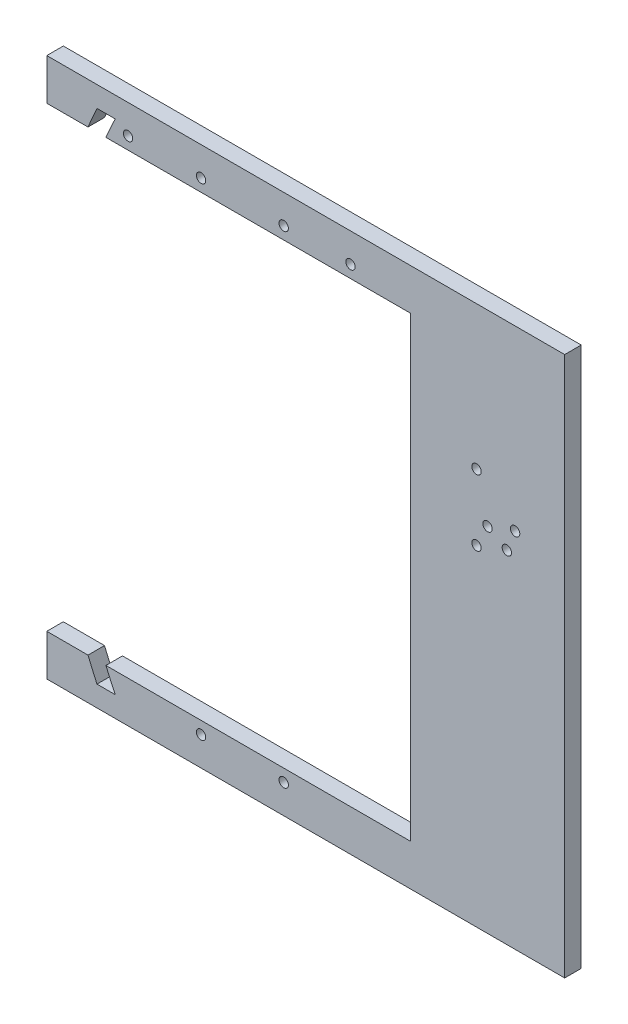
SolidWorks part; units mm, degrees
ref_plane "Front Plane" through (0, 0, 0) normal (0, 0, 1) x (1, 0, 0)
ref_plane "Top Plane" through (0, 0, 0) normal (0, 1, 0) x (1, 0, 0)
ref_plane "Right Plane" through (0, 0, 0) normal (1, 0, 0) x (0, 0, -1)
sketch "Bench Frame Sketch" plane through (0, 0, 0) normal (0, 0, 1) x (1, 0, 0)
  line L0 (-70, -98) -> (118, -98)
  line L1 (118, -98) -> (118, 98)
  line L2 (118, 98) -> (-70, 98)
  line L3 (-70, 98) -> (-70, 83)
  line L4 (-70, 83) -> (62, 83)
  line L5 (62, 83) -> (62, -83)
  line L6 (62, -83) -> (-70, -83)
  line L7 (-70, -83) -> (-70, -98)
  dimension "D1" = 70
  dimension "D2" = 118
  dimension "D3" = 62
  dimension "D4" = 98
  dimension "D5" = 98
  dimension "D6" = 83
  dimension "D7" = 83
extrude "Bench Frame Extrude" add sketch "Bench Frame Sketch" along normal mid plane 6
sketch "Curved Panel Clearance Sketch" plane through (0, 0, 0) normal (0, 0, 1) x (1, 0, 0)
  line L0 (-51.7777, 90.5) -> (-45.1596, 90.5)
  line L1 (-45.1596, -90.5) -> (-51.7777, -90.5)
  arc A0 (-51.7777, -90.5) -> (-51.7777, 90.5) centre (146, 0) cw
  arc A1 (-45.1596, 90.5) -> (-45.1596, -90.5) centre (146, 0) ccw
  dimension "D2" = 217.5
  dimension "D3" = 211.5
  dimension "D1" = 146
  dimension "D4" = 90.5
  dimension "D5" = 90.5
extrude "Curved Panel Clearance" cut sketch "Curved Panel Clearance Sketch" against normal mid plane 8
sketch "Pod Foot Clearance Sketch" plane through (0, 0, 0) normal (0, 0, 1) x (1, 0, 0)
  circle A0 centre (-14, -87.5) radius 1.7
  circle A1 centre (16, -87.5) radius 1.7
  circle A2 centre (-14, 87.5) radius 1.7
  circle A3 centre (16, 87.5) radius 1.7
  circle A4 centre (40.25, 87.5) radius 1.7
  circle A5 centre (-40.5, 87.5) radius 1.7
  circle A6 centre (86, 22) radius 1.7
  circle A7 centre (86, 46) radius 1.7
  circle A8 centre (90, 30) radius 1.7
  circle A9 centre (97, 26) radius 1.7
  circle A10 centre (100, 33.5) radius 1.7
  dimension "D3" = 3.4
  dimension "D6" = 3.4
  dimension "D9" = 3.4
  dimension "D12" = 3.4
  dimension "D15" = 3.4
  dimension "D18" = 3.4
  dimension "D21" = 3.4
  dimension "D24" = 3.4
  dimension "D27" = 3.4
  dimension "D30" = 3.4
  dimension "D33" = 3.4
  dimension "D1" = 14
  dimension "D2" = 87.5
  dimension "D4" = 16
  dimension "D5" = 87.5
  dimension "D7" = 14
  dimension "D8" = 87.5
  dimension "D10" = 16
  dimension "D11" = 87.5
  dimension "D13" = 40.25
  dimension "D14" = 87.5
  dimension "D16" = 40.5
  dimension "D17" = 87.5
  dimension "D19" = 86
  dimension "D20" = 22
  dimension "D22" = 86
  dimension "D23" = 46
  dimension "D25" = 90
  dimension "D26" = 30
  dimension "D28" = 97
  dimension "D29" = 26
  dimension "D31" = 100
  dimension "D32" = 33.5
extrude "Pod Foot Through Holes" cut sketch "Pod Foot Clearance Sketch" against normal mid plane 8
ref_plane "Bench Underside Plane" through (0, 0, -3) normal (0, 0, 1) x (1, 0, 0)
sketch "Foot Counterbore Sketch" plane through (0, 0, -3) normal (0, 0, 1) x (1, 0, 0)
  circle A0 centre (-14, -87.5) radius 3.6
  circle A1 centre (16, -87.5) radius 3.6
  circle A2 centre (-14, 87.5) radius 3.6
  circle A3 centre (16, 87.5) radius 3.6
  circle A4 centre (40.25, 87.5) radius 3.6
  circle A5 centre (-40.5, 87.5) radius 3.6
  circle A6 centre (86, 22) radius 3.6
  circle A7 centre (86, 46) radius 3.6
  circle A8 centre (90, 30) radius 3.6
  circle A9 centre (97, 26) radius 3.6
  circle A10 centre (100, 33.5) radius 3.6
  dimension "D1" = 14
  dimension "D2" = 87.5
  dimension "D4" = 16
  dimension "D5" = 87.5
  dimension "D7" = 14
  dimension "D8" = 87.5
  dimension "D10" = 16
  dimension "D11" = 87.5
  dimension "D13" = 40.25
  dimension "D14" = 87.5
  dimension "D16" = 40.5
  dimension "D17" = 87.5
  dimension "D19" = 86
  dimension "D20" = 22
  dimension "D22" = 86
  dimension "D23" = 46
  dimension "D25" = 90
  dimension "D26" = 30
  dimension "D28" = 97
  dimension "D29" = 26
  dimension "D31" = 100
  dimension "D32" = 33.5
  dimension "D3" = 7.2
  dimension "D6" = 7.2
  dimension "D9" = 7.2
  dimension "D12" = 7.2
  dimension "D15" = 7.2
  dimension "D18" = 7.2
  dimension "D21" = 7.2
  dimension "D24" = 7.2
  dimension "D27" = 7.2
  dimension "D30" = 7.2
  dimension "D33" = 7.2
extrude "Foot Counterbores" cut sketch "Foot Counterbore Sketch" along normal blind 2.9
equation "\"guard_front_foot_x\"= 14mm 'Front wall foot offset toward -X"
equation "\"guard_rear_foot_x\"= 16mm 'Rear wall foot offset toward +X"
equation "\"guard_foot_y\"= 87.5mm 'Wall and ear foot transverse location"
equation "\"inner_ear_foot_x\"= 40.25mm 'Inner ear foot at shaft pin"
equation "\"outer_ear_foot_x\"= 40.5mm 'Outer ear foot offset toward -X"
equation "\"tower_foot_1_x\"= 86mm 'Tower foot screw 1 X"
equation "\"tower_foot_1_y\"= 22mm 'Tower foot screw 1 Y"
equation "\"tower_foot_2_x\"= 86mm 'Tower foot screw 2 X"
equation "\"tower_foot_2_y\"= 46mm 'Tower foot screw 2 Y"
equation "\"tower_foot_3_x\"= 90mm 'Tower foot screw 3 X"
equation "\"tower_foot_3_y\"= 30mm 'Tower foot screw 3 Y"
equation "\"tower_foot_4_x\"= 97mm 'Tower foot screw 4 X"
equation "\"tower_foot_4_y\"= 26mm 'Tower foot screw 4 Y"
equation "\"tower_foot_5_x\"= 100mm 'Tower foot screw 5 X"
equation "\"tower_foot_5_y\"= 33.5mm 'Tower foot screw 5 Y"
equation "\"frame_left\"= 70mm 'Frame open end toward -X"
equation "\"frame_right\"= 118mm 'Frame closed end toward +X"
equation "\"frame_half_width\"= 98mm 'Bench frame half width"
equation "\"opening_end\"= 62mm 'Wheel opening closed end"
equation "\"opening_half_width\"= 83mm 'Wheel opening half width"
equation "\"bench_thickness\"= 6mm 'Bench frame plate thickness"
equation "\"panel_centre_x\"= 146mm 'Robot deck circle centre relative to wheel"
equation "\"relief_outer_radius\"= 217.5mm 'Outer guard panel clearance radius"
equation "\"relief_inner_radius\"= 211.5mm 'Inner guard panel clearance radius"
equation "\"relief_half_width\"= 90.5mm 'Transverse panel clearance extent"
equation "\"clearance_cut_depth\"= 8mm 'Relief cutter extends past both plate faces"
equation "\"screw_clearance\"= 3.4mm 'M3 foot screw clearance"
equation "\"counterbore_diameter\"= 7.2mm 'M3 pan head counterbore"
equation "\"counterbore_depth\"= 2.9mm 'Counterbore from underside"
equation "\"D1@Bench Frame Sketch\"= \"frame_left\""
equation "\"D2@Bench Frame Sketch\"= \"frame_right\""
equation "\"D3@Bench Frame Sketch\"= \"opening_end\""
equation "\"D4@Bench Frame Sketch\"= \"frame_half_width\""
equation "\"D5@Bench Frame Sketch\"= \"frame_half_width\""
equation "\"D6@Bench Frame Sketch\"= \"opening_half_width\""
equation "\"D7@Bench Frame Sketch\"= \"opening_half_width\""
equation "\"D1@Bench Frame Extrude\"= \"bench_thickness\""
equation "\"D1@Curved Panel Clearance Sketch\"= \"panel_centre_x\""
equation "\"D2@Curved Panel Clearance Sketch\"= \"relief_outer_radius\""
equation "\"D3@Curved Panel Clearance Sketch\"= \"relief_inner_radius\""
equation "\"D4@Curved Panel Clearance Sketch\"= \"relief_half_width\""
equation "\"D5@Curved Panel Clearance Sketch\"= \"relief_half_width\""
equation "\"D1@Curved Panel Clearance\"= \"clearance_cut_depth\""
equation "\"D1@Pod Foot Clearance Sketch\"= \"guard_front_foot_x\""
equation "\"D2@Pod Foot Clearance Sketch\"= \"guard_foot_y\""
equation "\"D3@Pod Foot Clearance Sketch\"= \"screw_clearance\""
equation "\"D4@Pod Foot Clearance Sketch\"= \"guard_rear_foot_x\""
equation "\"D5@Pod Foot Clearance Sketch\"= \"guard_foot_y\""
equation "\"D6@Pod Foot Clearance Sketch\"= \"screw_clearance\""
equation "\"D7@Pod Foot Clearance Sketch\"= \"guard_front_foot_x\""
equation "\"D8@Pod Foot Clearance Sketch\"= \"guard_foot_y\""
equation "\"D9@Pod Foot Clearance Sketch\"= \"screw_clearance\""
equation "\"D10@Pod Foot Clearance Sketch\"= \"guard_rear_foot_x\""
equation "\"D11@Pod Foot Clearance Sketch\"= \"guard_foot_y\""
equation "\"D12@Pod Foot Clearance Sketch\"= \"screw_clearance\""
equation "\"D13@Pod Foot Clearance Sketch\"= \"inner_ear_foot_x\""
equation "\"D14@Pod Foot Clearance Sketch\"= \"guard_foot_y\""
equation "\"D15@Pod Foot Clearance Sketch\"= \"screw_clearance\""
equation "\"D16@Pod Foot Clearance Sketch\"= \"outer_ear_foot_x\""
equation "\"D17@Pod Foot Clearance Sketch\"= \"guard_foot_y\""
equation "\"D18@Pod Foot Clearance Sketch\"= \"screw_clearance\""
equation "\"D19@Pod Foot Clearance Sketch\"= \"tower_foot_1_x\""
equation "\"D20@Pod Foot Clearance Sketch\"= \"tower_foot_1_y\""
equation "\"D21@Pod Foot Clearance Sketch\"= \"screw_clearance\""
equation "\"D22@Pod Foot Clearance Sketch\"= \"tower_foot_2_x\""
equation "\"D23@Pod Foot Clearance Sketch\"= \"tower_foot_2_y\""
equation "\"D24@Pod Foot Clearance Sketch\"= \"screw_clearance\""
equation "\"D25@Pod Foot Clearance Sketch\"= \"tower_foot_3_x\""
equation "\"D26@Pod Foot Clearance Sketch\"= \"tower_foot_3_y\""
equation "\"D27@Pod Foot Clearance Sketch\"= \"screw_clearance\""
equation "\"D28@Pod Foot Clearance Sketch\"= \"tower_foot_4_x\""
equation "\"D29@Pod Foot Clearance Sketch\"= \"tower_foot_4_y\""
equation "\"D30@Pod Foot Clearance Sketch\"= \"screw_clearance\""
equation "\"D31@Pod Foot Clearance Sketch\"= \"tower_foot_5_x\""
equation "\"D32@Pod Foot Clearance Sketch\"= \"tower_foot_5_y\""
equation "\"D33@Pod Foot Clearance Sketch\"= \"screw_clearance\""
equation "\"D1@Pod Foot Through Holes\"= \"clearance_cut_depth\""
equation "\"D1@Bench Underside Plane\"= \"bench_thickness\" / 2"
equation "\"D1@Foot Counterbore Sketch\"= \"guard_front_foot_x\""
equation "\"D2@Foot Counterbore Sketch\"= \"guard_foot_y\""
equation "\"D3@Foot Counterbore Sketch\"= \"counterbore_diameter\""
equation "\"D4@Foot Counterbore Sketch\"= \"guard_rear_foot_x\""
equation "\"D5@Foot Counterbore Sketch\"= \"guard_foot_y\""
equation "\"D6@Foot Counterbore Sketch\"= \"counterbore_diameter\""
equation "\"D7@Foot Counterbore Sketch\"= \"guard_front_foot_x\""
equation "\"D8@Foot Counterbore Sketch\"= \"guard_foot_y\""
equation "\"D9@Foot Counterbore Sketch\"= \"counterbore_diameter\""
equation "\"D10@Foot Counterbore Sketch\"= \"guard_rear_foot_x\""
equation "\"D11@Foot Counterbore Sketch\"= \"guard_foot_y\""
equation "\"D12@Foot Counterbore Sketch\"= \"counterbore_diameter\""
equation "\"D13@Foot Counterbore Sketch\"= \"inner_ear_foot_x\""
equation "\"D14@Foot Counterbore Sketch\"= \"guard_foot_y\""
equation "\"D15@Foot Counterbore Sketch\"= \"counterbore_diameter\""
equation "\"D16@Foot Counterbore Sketch\"= \"outer_ear_foot_x\""
equation "\"D17@Foot Counterbore Sketch\"= \"guard_foot_y\""
equation "\"D18@Foot Counterbore Sketch\"= \"counterbore_diameter\""
equation "\"D19@Foot Counterbore Sketch\"= \"tower_foot_1_x\""
equation "\"D20@Foot Counterbore Sketch\"= \"tower_foot_1_y\""
equation "\"D21@Foot Counterbore Sketch\"= \"counterbore_diameter\""
equation "\"D22@Foot Counterbore Sketch\"= \"tower_foot_2_x\""
equation "\"D23@Foot Counterbore Sketch\"= \"tower_foot_2_y\""
equation "\"D24@Foot Counterbore Sketch\"= \"counterbore_diameter\""
equation "\"D25@Foot Counterbore Sketch\"= \"tower_foot_3_x\""
equation "\"D26@Foot Counterbore Sketch\"= \"tower_foot_3_y\""
equation "\"D27@Foot Counterbore Sketch\"= \"counterbore_diameter\""
equation "\"D28@Foot Counterbore Sketch\"= \"tower_foot_4_x\""
equation "\"D29@Foot Counterbore Sketch\"= \"tower_foot_4_y\""
equation "\"D30@Foot Counterbore Sketch\"= \"counterbore_diameter\""
equation "\"D31@Foot Counterbore Sketch\"= \"tower_foot_5_x\""
equation "\"D32@Foot Counterbore Sketch\"= \"tower_foot_5_y\""
equation "\"D33@Foot Counterbore Sketch\"= \"counterbore_diameter\""
equation "\"D1@Foot Counterbores\"= \"counterbore_depth\""
